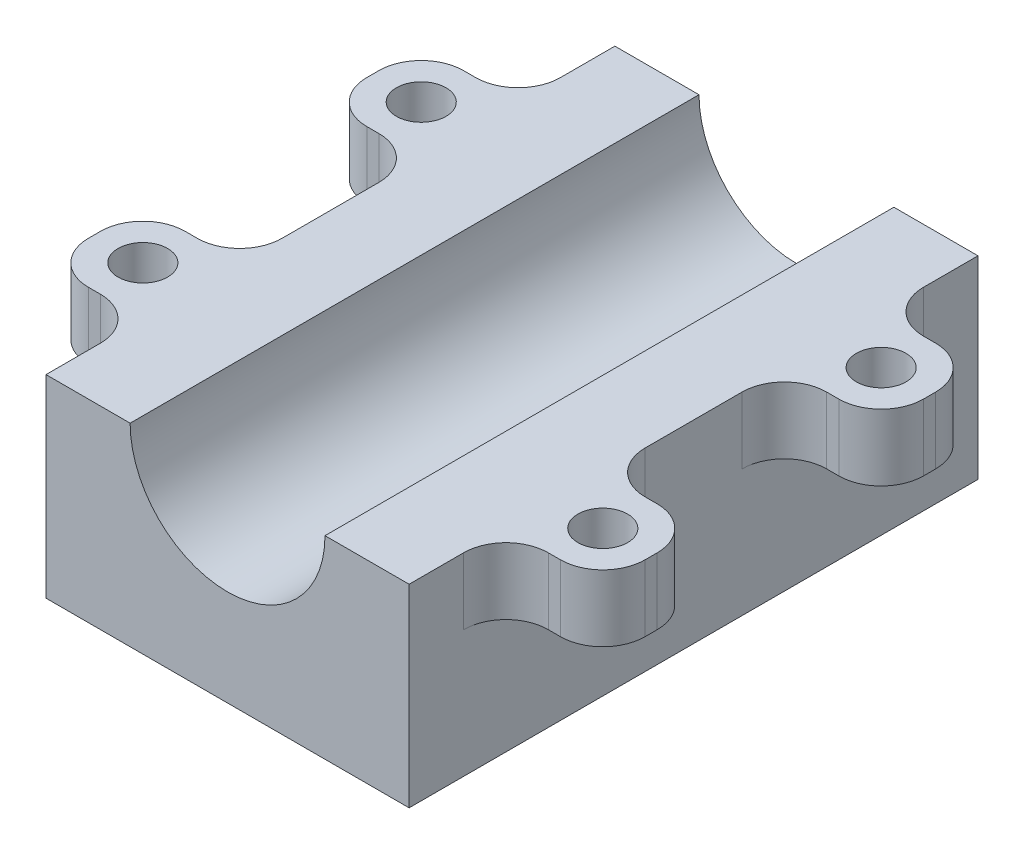
SolidWorks part; units mm, degrees
ref_plane "Front Plane" through (0, 0, 0) normal (0, 0, 1) x (1, 0, 0)
ref_plane "Top Plane" through (0, 0, 0) normal (0, 1, 0) x (1, 0, 0)
ref_plane "Right Plane" through (0, 0, 0) normal (1, 0, 0) x (0, 0, -1)
sketch "Sketch1" plane through (0, 0, 0) normal (0, 0, 1) x (1, 0, 0)
  line L1 (-15, -16) -> (15, -16)
  line L2 (-15, -16) -> (-15, 16)
  line L3 (-15, 16) -> (15, 16)
  line L4 (15, -16) -> (15, 16)
  line L5 (-15, -16) -> (15, 16) construction
  line L6 (-15, 16) -> (15, -16) construction
  circle A0 centre (0, 0) radius 8.05
  dimension "D1" = 16.1
  dimension "D2" = 30
  dimension "D3" = 32
extrude "Boss-Extrude1" add sketch "Sketch1" along normal blind 47
sketch "Sketch3" plane through (0, 0, 0) normal (0, 0, 1) x (1, 0, 0)
  line L0 (-15, 16) -> (-15, -16) construction
  line L1 (-15, 0) -> (15, 0)
  line L2 (-15, 0) -> (-15, 16)
  line L3 (-15, 16) -> (15, 16)
  line L4 (15, 0) -> (15, 16)
extrude "Cut-Extrude1" cut sketch "Sketch3" along normal through all both and the other way through all
sketch "Sketch4" plane through (0, 0, 0) normal (0, 1, 0) x (1, 0, 0)
  line L0 (15, -47) -> (15, 0) construction
  line L1 (15, -8) -> (23, -8)
  line L2 (15, -8) -> (15, -16)
  line L3 (15, -16) -> (23, -16)
  line L4 (23, -8) -> (23, -16)
  line L5 (8.05, 0) -> (15, 0) construction
  line L6 (-15, -39) -> (-23, -39)
  line L7 (0, 0) -> (0, 5.7091) construction
  line L8 (23, -39) -> (23, -31)
  line L9 (15, -31) -> (23, -31)
  line L10 (15, -39) -> (15, -31)
  line L11 (15, -39) -> (23, -39)
  line L12 (-15, -39) -> (-15, -31)
  line L13 (-15, -31) -> (-23, -31)
  line L14 (-23, -39) -> (-23, -31)
  line L15 (-23, -8) -> (-23, -16)
  line L16 (-15, -16) -> (-23, -16)
  line L17 (-15, -8) -> (-15, -16)
  line L18 (-15, -8) -> (-23, -8)
  line L19 (15, -23.5) -> (24.2871, -23.5) construction
  circle A0 centre (19, -12) radius 2.05
  circle A1 centre (19, -35) radius 2.05
  circle A2 centre (-19, -12) radius 2.05
  circle A3 centre (-19, -35) radius 2.05
  dimension "D4" = 4.1
  dimension "D1" = 8
  dimension "D2" = 8
  dimension "D3" = 8
extrude "Boss-Extrude2" add sketch "Sketch4" against normal blind 5.5
fillet "Fillet1" radius 3.5 16 edges at (15, -2.75, 16) (23, -2.75, 16) (23, -2.75, 8) (15, -2.75, 8) (15, -2.75, 31) (23, -2.75, 31) (23, -2.75, 39) (15, -2.75, 39) (-23, -2.75, 31) (-23, -2.75, 39) (-23, -2.75, 8) (-23, -2.75, 16) (-15, -2.75, 8) (-15, -2.75, 16) (-15, -2.75, 31) (-15, -2.75, 39)
